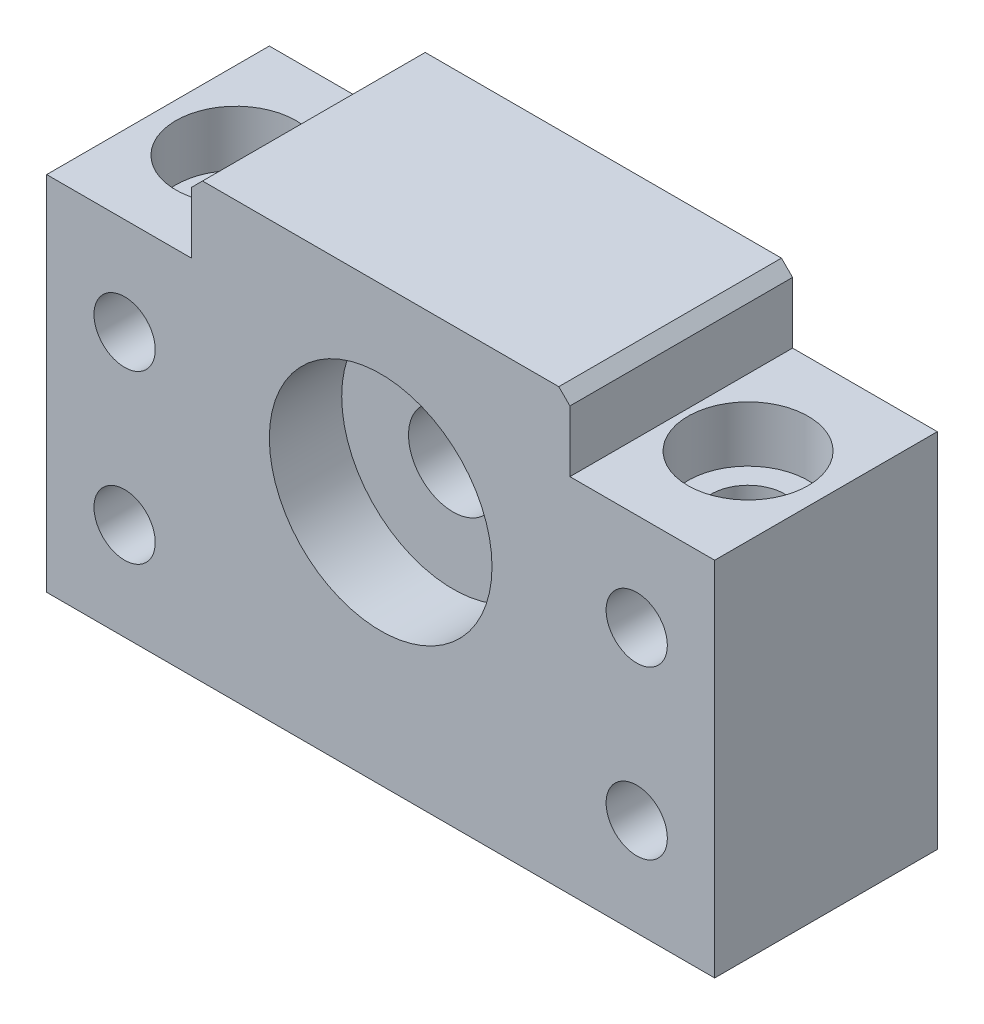
SolidWorks part; units mm, degrees
material "1.0037 (S235JR)"
ref_plane "Ebene vorne" through (0, 0, 0) normal (0, 0, 1) x (1, 0, 0)
ref_plane "Ebene oben" through (0, 0, 0) normal (0, 1, 0) x (1, 0, 0)
ref_plane "Ebene rechts" through (0, 0, 0) normal (1, 0, 0) x (0, 0, -1)
sketch "Skizze1" plane through (0, 0, 0) normal (0, 0, 1) x (1, 0, 0)
  line L0 (0, 0) -> (0, 46.2844) construction
  line L1 (-30, 0) -> (30, 0)
  line L2 (30, 0) -> (30, 32.5)
  line L3 (30, 32.5) -> (17, 32.5)
  line L4 (17, 32.5) -> (17, 38)
  line L5 (16, 39) -> (-16, 39)
  line L6 (17, 38) -> (16, 39)
  line L7 (-17, 38) -> (-16, 39)
  line L8 (-17, 32.5) -> (-17, 38)
  line L9 (-30, 32.5) -> (-17, 32.5)
  line L10 (-30, 0) -> (-30, 32.5)
  point P7 (17, 39)
  point P12 (0, 39)
  dimension "D1" = 60
  dimension "D2" = 34
  dimension "D4" = 32.5
  dimension "D5" = 39
extrude "Aufsatz-Linear austragen1" add sketch "Skizze1" along normal blind 20
sketch "Skizze4" plane through (0, 32.5, 0) normal (0, 1, 0) x (1, 0, 0)
  line L0 (0, 0) -> (0, -31.5995) construction
  line L1 (23, -10) -> (23, -23) construction
  line L2 (30, 0) -> (17, 0) construction
  circle A0 centre (23, -10) radius 3.3
  circle A2 centre (-23, -10) radius 3.3
  dimension "D1" = 46
  dimension "D2" = 10
  dimension "D3" = 6.6
extrude "Schnitt-Linear austragen2" cut sketch "Skizze4" against normal blind 50
sketch "Skizze5" plane through (0, 32.5, 0) normal (0, 1, 0) x (1, 0, 0)
  line L0 (0, 0) -> (0, -34.9473) construction
  circle A0 centre (23, -10) radius 5.4
  circle A3 centre (-23, -10) radius 5.4
  dimension "D1" = 10.8
extrude "Schnitt-Linear austragen3" cut sketch "Skizze5" against normal blind 5
sketch "Skizze6" plane through (0, 0, 20) normal (0, 0, 1) x (1, 0, 0)
  line L0 (0, 0) -> (0, 41.5676) construction
  line L1 (23, 23.75) -> (23, 8.75) construction
  line L3 (30, 16.25) -> (23, 16.25) construction
  line L4 (30, 0) -> (30, 32.5) construction
  circle A0 centre (23, 23.75) radius 2.75
  circle A1 centre (23, 8.75) radius 2.75
  circle A2 centre (-23, 23.75) radius 2.75
  circle A3 centre (-23, 8.75) radius 2.75
  dimension "D1" = 5.5
  dimension "D2" = 15
  dimension "D3" = 46
extrude "Schnitt-Linear austragen4" cut sketch "Skizze6" against normal blind 50
sketch "Skizze7" plane through (0, 0, 20) normal (0, 0, 1) x (1, 0, 0)
  line L0 (0, 0) -> (0, 41.4002) construction
  line L1 (-30, 0) -> (30, 0) construction
  circle A0 centre (0, 22) radius 4
  dimension "D1" = 8
  dimension "D2" = 22
extrude "Schnitt-Linear austragen5" cut sketch "Skizze7" against normal blind 50
sketch "Skizze8" plane through (0, 0, 20) normal (0, 0, 1) x (1, 0, 0)
  circle A0 centre (0, 22) radius 10
  dimension "D1" = 20
extrude "Schnitt-Linear austragen6" cut sketch "Skizze8" against normal blind 6.5
sketch "Skizze9" plane through (0, 0, 0) normal (0, 0, -1) x (-1, 0, 0)
  circle A0 centre (0, 22) radius 10 construction
  circle A1 centre (0, 22) radius 10
extrude "Schnitt-Linear austragen7" cut sketch "Skizze9" against normal blind 6.5
